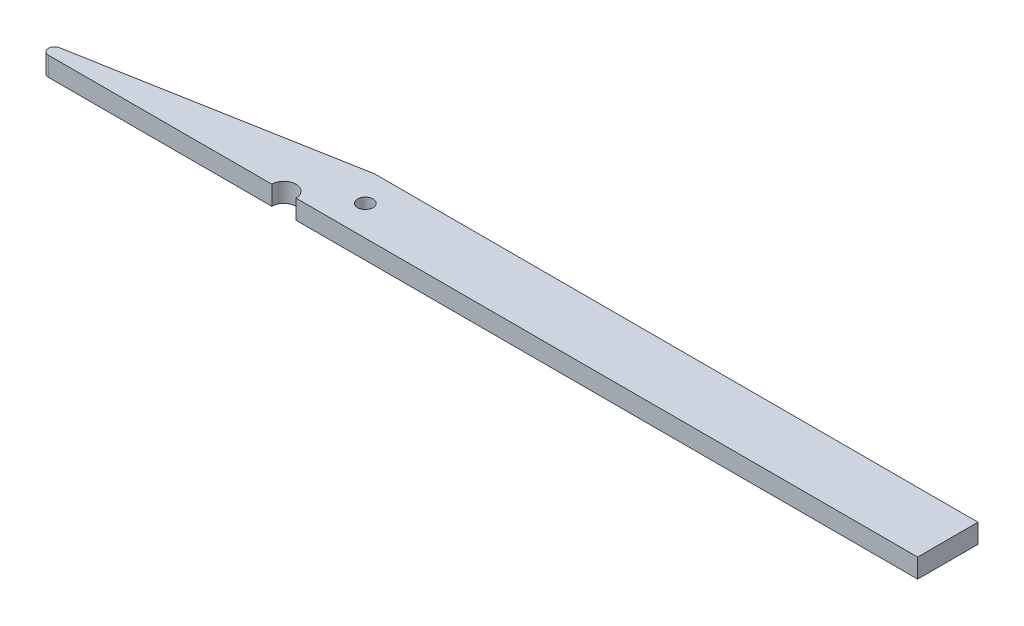
SolidWorks part; units mm, degrees
ref_plane "Front Plane" through (0, 0, 0) normal (0, 0, 1) x (1, 0, 0)
ref_plane "Top Plane" through (0, 0, 0) normal (0, 1, 0) x (1, 0, 0)
ref_plane "Right Plane" through (0, 0, 0) normal (1, 0, 0) x (0, 0, -1)
sketch "Sketch1" plane through (0, 0, 0) normal (0, 1, 0) x (1, 0, 0)
  line L0 (0, 0) -> (-224.004, 0)
  line L1 (-180, 10) -> (0, 10)
  line L2 (-180, 10) -> (-224.1825, 1.9839)
  arc A1 (0, 0) -> (0, 10) centre (0, 5) ccw
  arc A2 (-224.004, 0) -> (-224.1825, 1.9839) centre (-224.004, 1) cw
  point P8 (5, 5)
  point P9 (-225, 0.9104)
  dimension "D1" = 1
  dimension "D2" = 230
  dimension "D3" = 10
  dimension "D4" = 180
extrude "Boss-Extrude1" add sketch "Sketch1" along normal blind 3.175
sketch "Sketch2" plane through (0, 3.175, 0) normal (0, 1, 0) x (1, 0, 0)
  circle A0 centre (-50, 5) radius 1.27
  circle A1 centre (0, 5) radius 1.27
  arc A2 (0, 0) -> (0, 10) centre (0, 5) ccw construction
  circle A3 centre (-176.52, 5) radius 1.27
  dimension "D1" = 2.54
  dimension "D2" = 2.54
  dimension "D4" = 2.54
  dimension "D3" = 50
  dimension "D5" = 126.52
extrude "Cut-Extrude1" cut sketch "Sketch2" against normal up to next
sketch "Sketch3" plane through (0, 3.175, 0) normal (0, 1, 0) x (1, 0, 0)
  line L0 (-224.004, 0) -> (0, 0) construction
  line L1 (-187, 0) -> (-183, 0)
  arc A0 (-187, 0) -> (-183, 0) centre (-185, 0) cw
  dimension "D1" = 2
  dimension "D2" = 185
extrude "Cut-Extrude2" cut sketch "Sketch3" against normal through all
sketch "Sketch4" plane through (0, 0, 0) normal (0, -1, 0) x (1, 0, 0)
  line L0 (-183, 0) -> (0, 0) construction
  line L1 (-80, 0) -> (5, 0)
  line L2 (-80, 0) -> (-80, -10)
  line L3 (-80, -10) -> (5, -10)
  line L4 (5, 0) -> (5, -10)
  line L5 (0, -10) -> (-180, -10) construction
  arc A0 (0, -10) -> (0, 0) centre (0, -5) ccw construction
  point P11 (5, -5)
  dimension "D1" = 85
extrude "Cut-Extrude3" cut sketch "Sketch4" against normal through all
